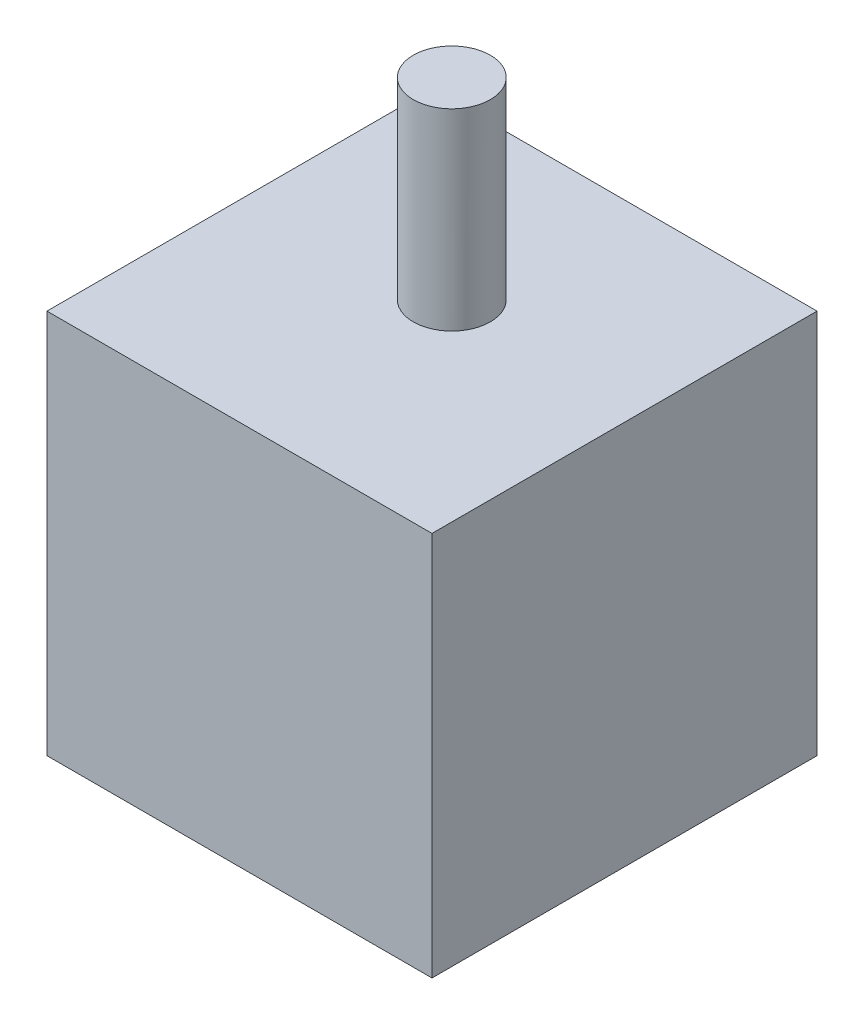
SolidWorks part; units mm, degrees
ref_plane "Front Plane" through (0, 0, 0) normal (0, 0, 1) x (1, 0, 0)
ref_plane "Top Plane" through (0, 0, 0) normal (0, 1, 0) x (1, 0, 0)
ref_plane "Right Plane" through (0, 0, 0) normal (1, 0, 0) x (0, 0, -1)
sketch "Sketch1" plane through (0, 0, 0) normal (0, 0, 1) x (1, 0, 0)
  line L1 (-13.5151, 6.2347) -> (6.4849, 6.2347)
  line L2 (-13.5151, 6.2347) -> (-13.5151, -13.7653)
  line L3 (-13.5151, -13.7653) -> (6.4849, -13.7653)
  line L4 (6.4849, 6.2347) -> (6.4849, -13.7653)
  dimension "D1" = 20
  dimension "D2" = 20
extrude "Boss-Extrude1" add sketch "Sketch1" along normal blind 20
sketch "Sketch2" plane through (0, 6.2347, 0) normal (0, 1, 0) x (1, 0, 0)
  circle A0 centre (-3.5151, -8.9719) radius 2
extrude "Boss-Extrude2" add sketch "Sketch2" along normal blind 10
